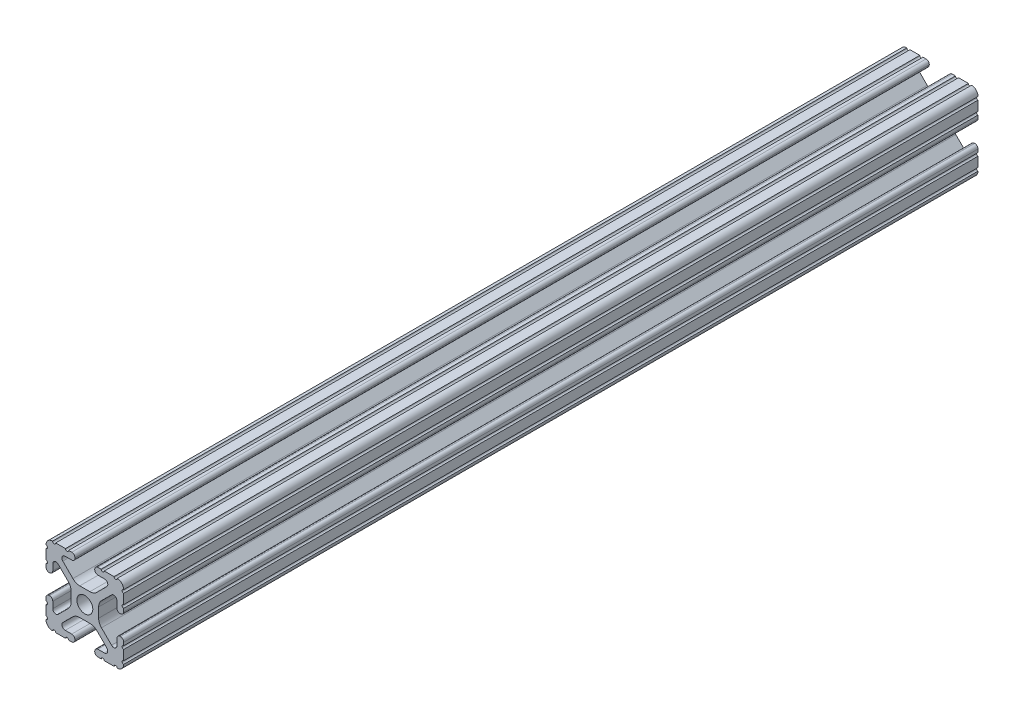
SolidWorks part; units mm, degrees
ref_plane "Front Plane" through (0, 0, 0) normal (0, 0, 1) x (1, 0, 0)
ref_plane "Top Plane" through (0, 0, 0) normal (0, 1, 0) x (1, 0, 0)
ref_plane "Right Plane" through (0, 0, 0) normal (1, 0, 0) x (0, 0, -1)
sketch "Sketch1" plane through (0, 0, 0) normal (0, 0, 1) x (1, 0, 0)
  line L88 (-7.1797, -8.6452) -> (-3.9523, -5.4237)
  line L89 (-1.7093, -4.4958) -> (1.7093, -4.4958)
  line L90 (3.9523, -5.4237) -> (7.1797, -8.6452)
  line L91 (6.4164, -10.4902) -> (4.2875, -10.4902)
  line L92 (3.2385, -11.5392) -> (3.2385, -11.651)
  line L93 (4.2875, -12.7) -> (5.3171, -12.7)
  line L94 (6.3331, -12.7) -> (9.5504, -12.7)
  line L95 (12.7, -9.5504) -> (12.7, -6.3331)
  line L96 (12.7, -5.3171) -> (12.7, -4.2875)
  line L97 (11.651, -3.2385) -> (11.5392, -3.2385)
  line L98 (10.4902, -4.2875) -> (10.4902, -6.4021)
  line L99 (8.7371, -7.1294) -> (5.441, -3.8408)
  line L100 (4.5085, -1.5932) -> (4.5085, 1.5932)
  line L101 (5.441, 3.8408) -> (8.7371, 7.1294)
  line L102 (10.4902, 6.4021) -> (10.4902, 4.2875)
  line L103 (11.5392, 3.2385) -> (11.651, 3.2385)
  line L104 (12.7, 4.2875) -> (12.7, 5.3171)
  line L105 (12.7, 6.3331) -> (12.7, 9.5504)
  line L106 (9.5504, 12.7) -> (6.3331, 12.7)
  line L107 (5.3171, 12.7) -> (4.2875, 12.7)
  line L108 (3.2385, 11.651) -> (3.2385, 11.5392)
  line L109 (4.2875, 10.4902) -> (6.4768, 10.4902)
  line L110 (7.207, 8.7244) -> (3.8983, 5.4232)
  line L111 (1.6558, 4.4958) -> (-1.6558, 4.4958)
  line L112 (-3.8983, 5.4232) -> (-7.207, 8.7244)
  line L113 (-6.4768, 10.4902) -> (-4.2875, 10.4902)
  line L114 (-3.2385, 11.5392) -> (-3.2385, 11.651)
  line L115 (-4.2875, 12.7) -> (-5.3171, 12.7)
  line L116 (-6.3331, 12.7) -> (-9.5504, 12.7)
  line L117 (-12.7, 9.5504) -> (-12.7, 6.3331)
  line L118 (-12.7, 5.3171) -> (-12.7, 4.2875)
  line L119 (-11.651, 3.2385) -> (-11.5392, 3.2385)
  line L120 (-10.4902, 4.2875) -> (-10.4902, 6.4021)
  line L121 (-8.7371, 7.1294) -> (-5.441, 3.8408)
  line L122 (-4.5085, 1.5932) -> (-4.5085, -1.5932)
  line L123 (-5.441, -3.8408) -> (-8.7371, -7.1294)
  line L124 (-10.4902, -6.4021) -> (-10.4902, -4.2875)
  line L125 (-11.5392, -3.2385) -> (-11.651, -3.2385)
  line L126 (-12.7, -4.2875) -> (-12.7, -5.3171)
  line L127 (-12.7, -6.3331) -> (-12.7, -9.5504)
  line L128 (-9.5504, -12.7) -> (-6.3331, -12.7)
  line L129 (-5.3171, -12.7) -> (-4.2875, -12.7)
  line L130 (-3.2385, -11.651) -> (-3.2385, -11.5392)
  line L131 (-4.2875, -10.4902) -> (-6.4164, -10.4902)
  circle A1 centre (0, 0) radius 2.6035
  arc A104 (-7.1797, -8.6452) -> (-6.4164, -10.4902) centre (-6.4164, -9.4098) ccw
  arc A105 (-1.7093, -4.4958) -> (-3.9523, -5.4237) centre (-1.7093, -7.6708) ccw
  arc A106 (3.9523, -5.4237) -> (1.7093, -4.4958) centre (1.7093, -7.6708) ccw
  arc A107 (6.4164, -10.4902) -> (7.1797, -8.6452) centre (6.4164, -9.4098) ccw
  arc A108 (4.2875, -10.4902) -> (3.2385, -11.5392) centre (4.2875, -11.5392) ccw
  arc A109 (3.2385, -11.651) -> (4.2875, -12.7) centre (4.2875, -11.651) ccw
  arc A110 (6.3331, -12.7) -> (5.3171, -12.7) centre (5.8251, -12.7) ccw
  arc A111 (10.5664, -12.6998) -> (9.5504, -12.7) centre (10.0584, -12.7) ccw
  arc A112 (10.5664, -12.6998) -> (12.6998, -10.5664) centre (10.5918, -10.5918) ccw
  arc A113 (12.7, -9.5504) -> (12.6998, -10.5664) centre (12.7, -10.0584) ccw
  arc A114 (12.7, -5.3171) -> (12.7, -6.3331) centre (12.7, -5.8251) ccw
  arc A115 (12.7, -4.2875) -> (11.651, -3.2385) centre (11.651, -4.2875) ccw
  arc A116 (11.5392, -3.2385) -> (10.4902, -4.2875) centre (11.5392, -4.2875) ccw
  arc A117 (8.7371, -7.1294) -> (10.4902, -6.4021) centre (9.4628, -6.4021) ccw
  arc A118 (4.5085, -1.5932) -> (5.441, -3.8408) centre (7.6835, -1.5932) ccw
  arc A119 (5.441, 3.8408) -> (4.5085, 1.5932) centre (7.6835, 1.5932) ccw
  arc A120 (10.4902, 6.4021) -> (8.7371, 7.1294) centre (9.4628, 6.4021) ccw
  arc A121 (10.4902, 4.2875) -> (11.5392, 3.2385) centre (11.5392, 4.2875) ccw
  arc A122 (11.651, 3.2385) -> (12.7, 4.2875) centre (11.651, 4.2875) ccw
  arc A123 (12.7, 6.3331) -> (12.7, 5.3171) centre (12.7, 5.8251) ccw
  arc A124 (12.6998, 10.5664) -> (12.7, 9.5504) centre (12.7, 10.0584) ccw
  arc A125 (12.6998, 10.5664) -> (10.5664, 12.6998) centre (10.5918, 10.5918) ccw
  arc A126 (9.5504, 12.7) -> (10.5664, 12.6998) centre (10.0584, 12.7) ccw
  arc A127 (5.3171, 12.7) -> (6.3331, 12.7) centre (5.8251, 12.7) ccw
  arc A128 (4.2875, 12.7) -> (3.2385, 11.651) centre (4.2875, 11.651) ccw
  arc A129 (3.2385, 11.5392) -> (4.2875, 10.4902) centre (4.2875, 11.5392) ccw
  arc A130 (7.207, 8.7244) -> (6.4768, 10.4902) centre (6.4768, 9.4563) ccw
  arc A131 (1.6558, 4.4958) -> (3.8983, 5.4232) centre (1.6558, 7.6708) ccw
  arc A132 (-3.8983, 5.4232) -> (-1.6558, 4.4958) centre (-1.6558, 7.6708) ccw
  arc A133 (-6.4768, 10.4902) -> (-7.207, 8.7244) centre (-6.4768, 9.4563) ccw
  arc A134 (-4.2875, 10.4902) -> (-3.2385, 11.5392) centre (-4.2875, 11.5392) ccw
  arc A135 (-3.2385, 11.651) -> (-4.2875, 12.7) centre (-4.2875, 11.651) ccw
  arc A136 (-6.3331, 12.7) -> (-5.3171, 12.7) centre (-5.8251, 12.7) ccw
  arc A137 (-10.5664, 12.6998) -> (-9.5504, 12.7) centre (-10.0584, 12.7) ccw
  arc A138 (-10.5664, 12.6998) -> (-12.6998, 10.5664) centre (-10.5918, 10.5918) ccw
  arc A139 (-12.7, 9.5504) -> (-12.6998, 10.5664) centre (-12.7, 10.0584) ccw
  arc A140 (-12.7, 5.3171) -> (-12.7, 6.3331) centre (-12.7, 5.8251) ccw
  arc A141 (-12.7, 4.2875) -> (-11.651, 3.2385) centre (-11.651, 4.2875) ccw
  arc A142 (-11.5392, 3.2385) -> (-10.4902, 4.2875) centre (-11.5392, 4.2875) ccw
  arc A143 (-8.7371, 7.1294) -> (-10.4902, 6.4021) centre (-9.4628, 6.4021) ccw
  arc A144 (-4.5085, 1.5932) -> (-5.441, 3.8408) centre (-7.6835, 1.5932) ccw
  arc A145 (-5.441, -3.8408) -> (-4.5085, -1.5932) centre (-7.6835, -1.5932) ccw
  arc A146 (-10.4902, -6.4021) -> (-8.7371, -7.1294) centre (-9.4628, -6.4021) ccw
  arc A147 (-10.4902, -4.2875) -> (-11.5392, -3.2385) centre (-11.5392, -4.2875) ccw
  arc A148 (-11.651, -3.2385) -> (-12.7, -4.2875) centre (-11.651, -4.2875) ccw
  arc A149 (-12.7, -6.3331) -> (-12.7, -5.3171) centre (-12.7, -5.8251) ccw
  arc A150 (-12.6998, -10.5664) -> (-12.7, -9.5504) centre (-12.7, -10.0584) ccw
  arc A151 (-12.6998, -10.5664) -> (-10.5664, -12.6998) centre (-10.5918, -10.5918) ccw
  arc A152 (-9.5504, -12.7) -> (-10.5664, -12.6998) centre (-10.0584, -12.7) ccw
  arc A153 (-5.3171, -12.7) -> (-6.3331, -12.7) centre (-5.8251, -12.7) ccw
  arc A154 (-4.2875, -12.7) -> (-3.2385, -11.651) centre (-4.2875, -11.651) ccw
  arc A155 (-3.2385, -11.5392) -> (-4.2875, -10.4902) centre (-4.2875, -11.5392) ccw
extrude "Boss-Extrude1" add sketch "Sketch1" along normal mid plane 279.4
